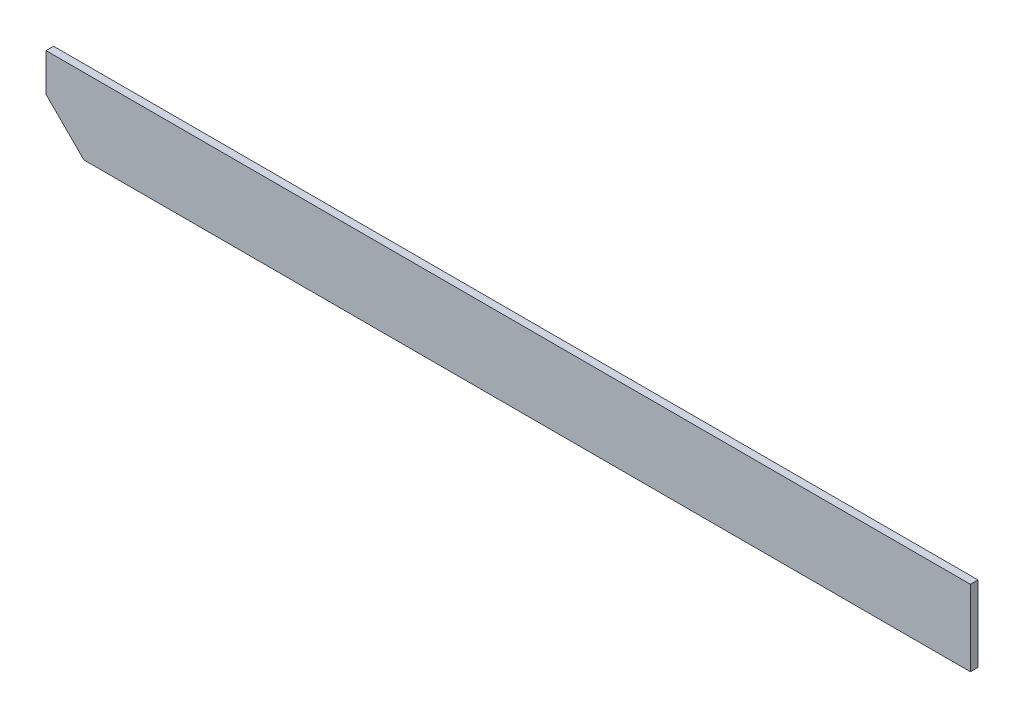
SolidWorks part; units mm, degrees
material "Q235A"
ref_plane "前视" through (0, 0, 0) normal (0, 0, 1) x (1, 0, 0)
ref_plane "上视" through (0, 0, 0) normal (0, 1, 0) x (1, 0, 0)
ref_plane "右视" through (0, 0, 0) normal (1, 0, 0) x (0, 0, -1)
sketch "草图1" plane through (0, 0, 0) normal (0, 0, 1) x (1, 0, 0)
  line L1 (610, -50) -> (-610, -50)
  line L2 (610, -50) -> (610, 50)
  line L3 (610, 50) -> (-610, 50)
  line L4 (-610, -50) -> (-610, 50)
  line L5 (610, -50) -> (-610, 50) construction
  line L6 (610, 50) -> (-610, -50) construction
  point P0 (0, 0)
  dimension "D1" = 100
  dimension "D2" = 1220
extrude "凸台-拉伸1" add sketch "草图1" along normal blind 10
chamfer "倒角1" distance 50 angle 45 1 edges at (-610, -50, 5)
